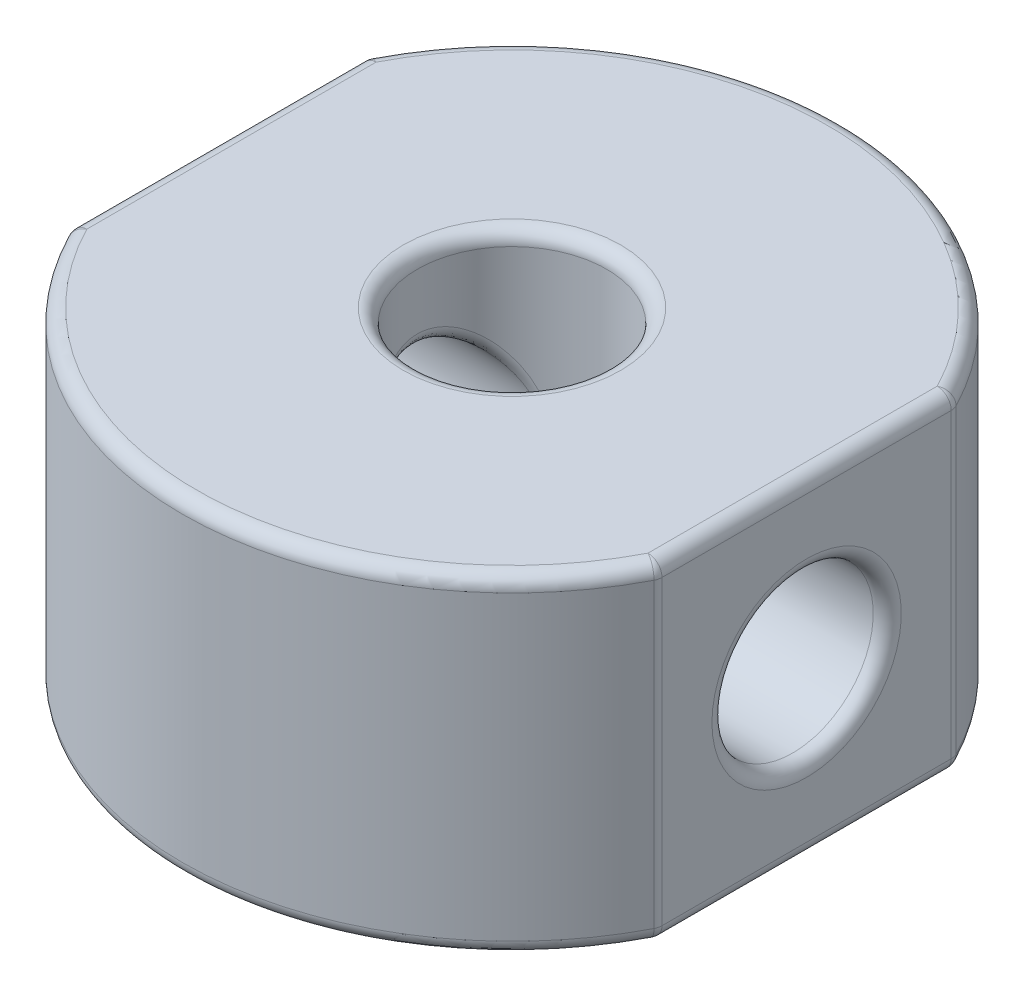
SolidWorks part; units mm, degrees
ref_plane "Front Plane" through (0, 0, 0) normal (0, 0, 1) x (1, 0, 0)
ref_plane "Top Plane" through (0, 0, 0) normal (0, 1, 0) x (1, 0, 0)
ref_plane "Right Plane" through (0, 0, 0) normal (1, 0, 0) x (0, 0, -1)
sketch "Sketch1" plane through (0, 0, 0) normal (0, 1, 0) x (1, 0, 0)
  line L0 (-2.7, 0) -> (-8.4, 0) construction
  line L1 (2.7, 0) -> (8.4, 0) construction
  line L2 (8.4, -4.219) -> (8.4, 4.219)
  line L3 (-8.4, -4.219) -> (-8.4, 4.219)
  line L4 (-8.4, 0) -> (-9.4, 0) construction
  circle A0 centre (0, 0) radius 9.4
  circle A1 centre (0, 0) radius 2.7
  point P11 (8.4, 0)
  point P14 (-8.4, 0)
  dimension "D1" = 5.4
  dimension "D2" = 5.7
  dimension "D3" = 1
extrude "Boss-Extrude1" add sketch "Sketch1" along normal blind 9.4 contours L2 A0 L3 A1
sketch "Sketch2" plane through (-8.4, 0, 0) normal (-1, 0, 0) x (0, 0, 1)
  line L0 (-4.219, 4.7) -> (0, 4.7) construction
  line L1 (-4.219, 9.4) -> (-4.219, 0) construction
  circle A0 centre (0, 4.7) radius 2.3
  point P3 (-1.7558, 4.7)
  point P8 (0, 0)
  dimension "D1" = 4.6
extrude "Cut-Extrude1" cut sketch "Sketch2" against normal through all
fillet "Fillet1" radius 0.4 18 edges at (-8.4, 4.7, 4.219) (-8.4, 4.7, -4.219) (8.4, 4.7, -4.219) (8.4, 4.7, 4.219) (0, 0, 9.4) (0, 0, -9.4) (-8.4, 0, 0) (8.4, 0, 0) (0, 0, 2.7) (0, 9.4, -9.4) (0, 9.4, 9.4) (-8.4, 9.4, 0) (8.4, 9.4, 0) (0, 9.4, 2.7) (8.4, 4.7, 2.3) (1.4459, 4.3988, -2.2802) (-1.4459, 5.0012, -2.2802) (-8.4, 4.7, 2.3)
